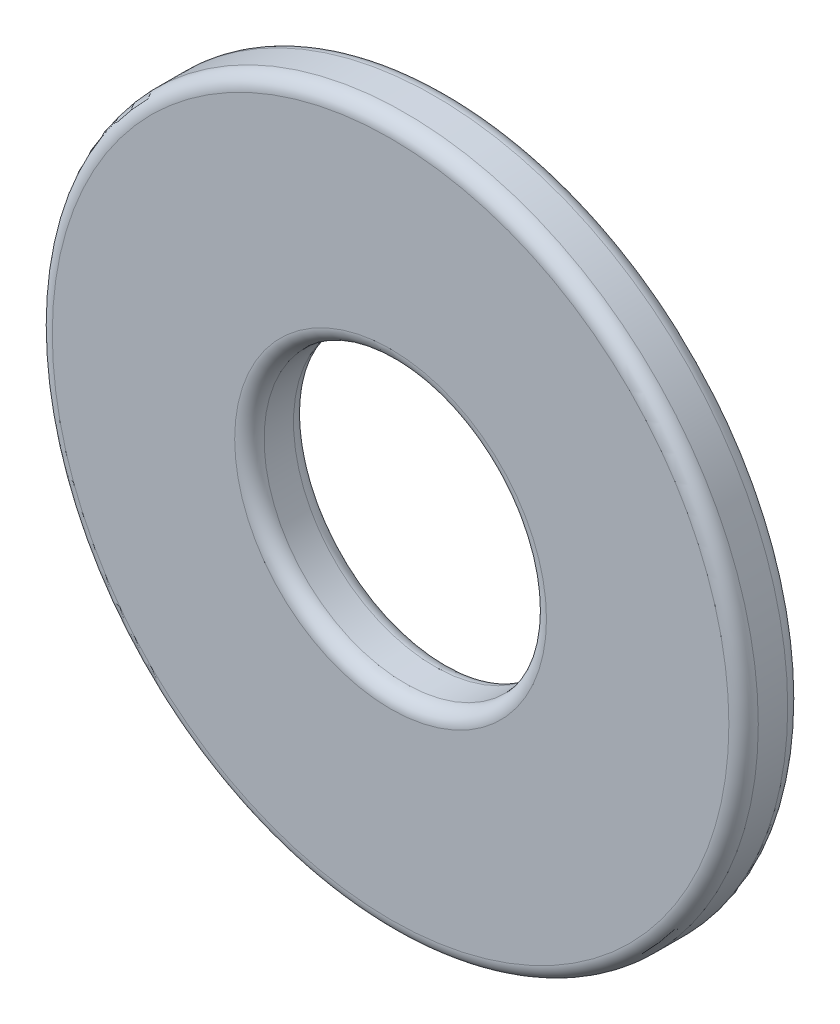
SolidWorks part; units mm, degrees
material "Wrought Stainless Steel"
ref_plane "Front Plane" through (0, 0, 0) normal (0, 0, 1) x (1, 0, 0)
ref_plane "Top Plane" through (0, 0, 0) normal (0, 1, 0) x (1, 0, 0)
ref_plane "Right Plane" through (0, 0, 0) normal (1, 0, 0) x (0, 0, -1)
sketch "Sketch1" plane through (0, 0, 0) normal (0, 0, 1) x (1, 0, 0)
  circle A0 centre (0, 0) radius 9.525
  circle A1 centre (0, 0) radius 3.81
  dimension "D1" = 19.05
  dimension "D2" = 7.62
extrude "Boss-Extrude1" add sketch "Sketch1" along normal blind 1.5875
fillet "Fillet1" radius 0.3969 4 edges at (3.81, 0, 0) (9.525, 0, 0) (3.81, 0, 1.5875) (9.525, 0, 1.5875)
